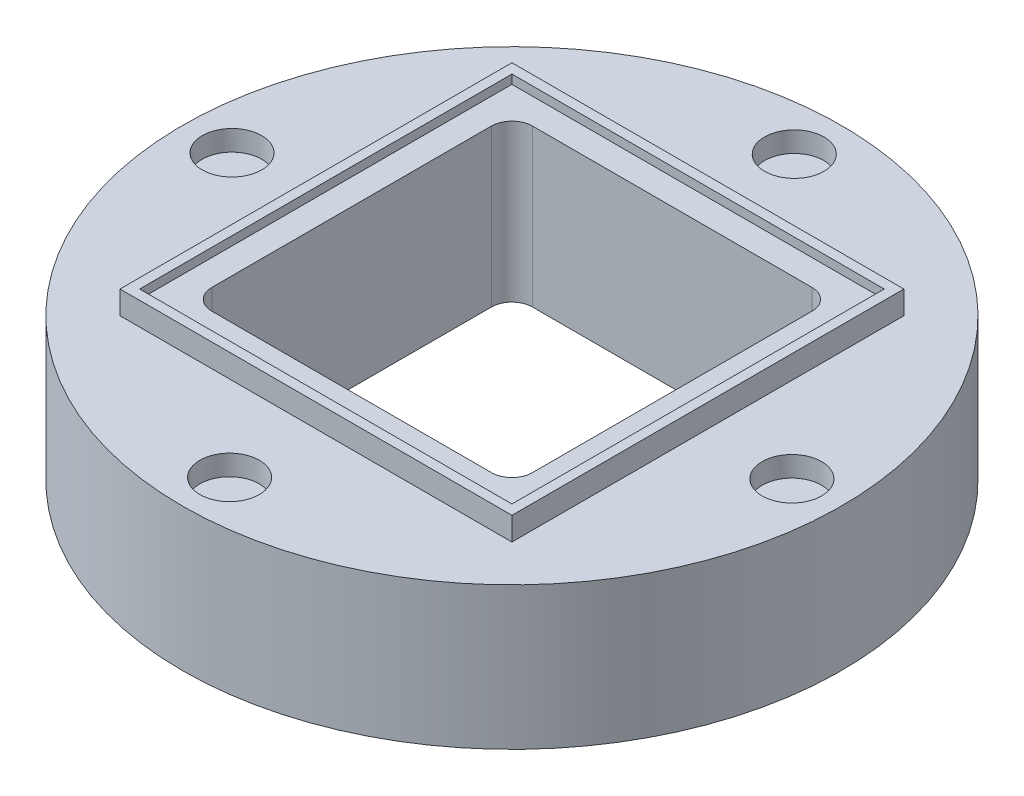
SolidWorks part; units mm, degrees
material "ABS"
ref_plane "Front Plane" through (0, 0, 0) normal (0, 0, 1) x (1, 0, 0)
ref_plane "Top Plane" through (0, 0, 0) normal (0, 1, 0) x (1, 0, 0)
ref_plane "Right Plane" through (0, 0, 0) normal (1, 0, 0) x (0, 0, -1)
sketch "Sketch1" plane through (0, 0, 0) normal (0, 1, 0) x (1, 0, 0)
  circle A0 centre (0, 0) radius 18.5
  dimension "D1" = 37
extrude "Boss-Extrude1" add sketch "Sketch1" along normal blind 8
sketch "Sketch11" plane through (0, 8, 0) normal (0, 1, 0) x (1, 0, 0)
  line L0 (0, 18.5) -> (0, 17.45) construction
  circle A0 centre (0, 0) radius 18.5 construction
  circle A1 centre (0.0668, 15.7813) radius 1.67
  dimension "D2" = 3.34
  dimension "D1" = 1.05
extrude "Cut-Extrude5" cut sketch "Sketch11" against normal blind 1.15
pattern_circular "CirPattern1" count 4 over 360 about axis through (0, 0, 0) along (0, 1, 0) of "Cut-Extrude5"
sketch "Sketch13" plane through (0, 8, 0) normal (0, 1, 0) x (1, 0, 0)
  line L1 (11, -11) -> (-11, -11)
  line L2 (11, -11) -> (11, 11)
  line L3 (11, 11) -> (-11, 11)
  line L4 (-11, -11) -> (-11, 11)
  line L5 (11, -11) -> (-11, 11) construction
  line L6 (11, 11) -> (-11, -11) construction
  line L7 (10.45, -10.45) -> (-10.45, -10.45)
  line L8 (10.45, -10.45) -> (10.45, 10.45)
  line L9 (10.45, 10.45) -> (-10.45, 10.45)
  line L10 (-10.45, -10.45) -> (-10.45, 10.45)
  line L11 (10.45, -10.45) -> (-10.45, 10.45) construction
  line L12 (10.45, 10.45) -> (-10.45, -10.45) construction
  point P0 (0, 0)
  point P7 (0, 0)
  point P28 (0, 0)
  dimension "D1" = 22
  dimension "D3" = 20.9
extrude "Boss-Extrude3" add sketch "Sketch13" along normal blind 1.3 contours L4 L1 L2 L3 L7 L10 L9 L8
sketch "Sketch12" plane through (0, 8, 0) normal (0, 1, 0) x (1, 0, 0)
  line L0 (11, -11) -> (11, 11) construction
  line L1 (-11, 11) -> (11, 11)
  line L2 (-11, 11) -> (-11, -11)
  line L3 (-11, -11) -> (11, -11)
  line L4 (11, 11) -> (11, -11)
  line L5 (-11, 11) -> (11, -11) construction
  line L6 (-11, -11) -> (11, 11) construction
  point P0 (0, 0)
  point P1 (0, 0)
extrude "Boss-Extrude2" add sketch "Sketch12" along normal blind 0.8
sketch "Sketch14" plane through (0, 8.8, 0) normal (0, 1, 0) x (1, 0, 0)
  line L0 (7.85, 9) -> (7.85, 7.85) construction
  line L1 (-9, -9) -> (9, -9)
  line L2 (-9, -9) -> (-9, 9)
  line L3 (-9, 9) -> (9, 9)
  line L4 (9, -9) -> (9, 9)
  line L5 (-9, -9) -> (9, 9) construction
  line L6 (-9, 9) -> (9, -9) construction
  line L7 (7.85, 7.85) -> (9, 7.85) construction
  arc A0 (7.85, 9) -> (9, 7.85) centre (7.85, 7.85) cw
  arc A1 (9, -7.85) -> (7.85, -9) centre (7.85, -7.85) cw
  arc A2 (-7.85, -9) -> (-9, -7.85) centre (-7.85, -7.85) cw
  arc A3 (-9, 7.85) -> (-7.85, 9) centre (-7.85, 7.85) cw
  point P0 (0, 0)
  point P22 (0, 0)
  dimension "D1" = 18
  dimension "D2" = 18
  dimension "D3" = 1.15
  dimension "D4" = 4
extrude "Cut-Extrude6" cut sketch "Sketch14" against normal through all contours A3 L2 A2 L1 A1 L4 A0 L3
